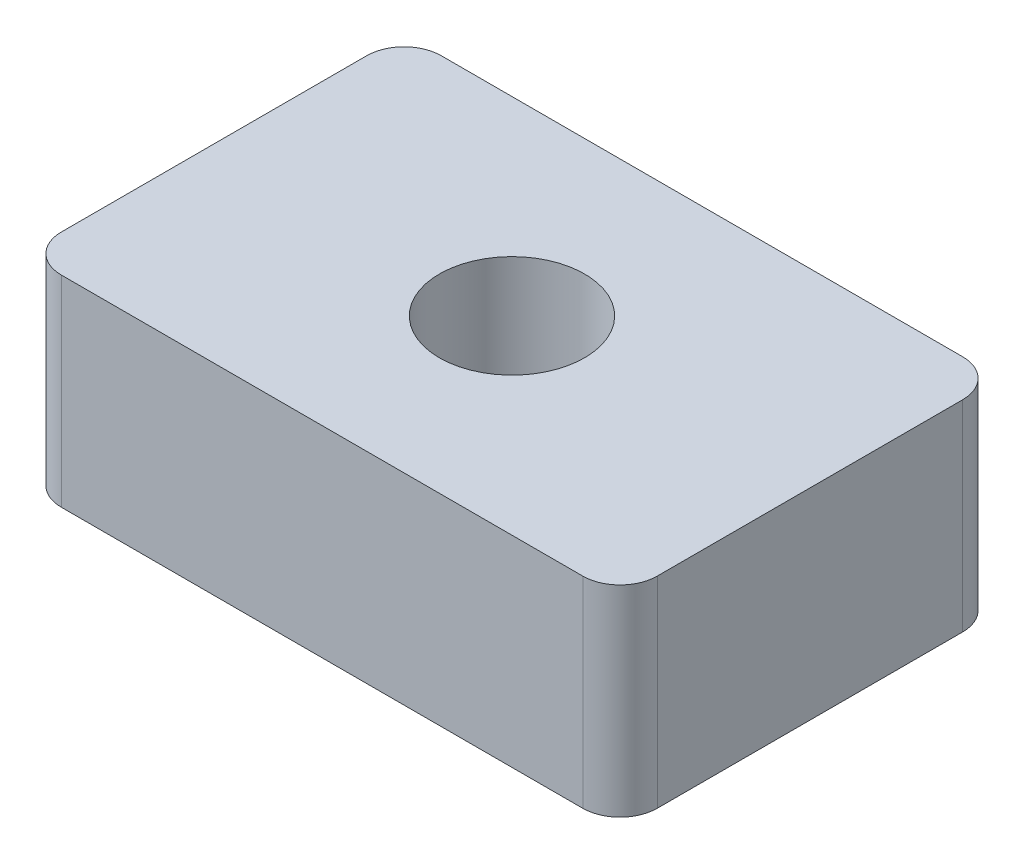
SolidWorks part; units mm, degrees
ref_plane "Alzado" through (0, 0, 0) normal (0, 0, 1) x (1, 0, 0)
ref_plane "Planta" through (0, 0, 0) normal (0, 1, 0) x (1, 0, 0)
ref_plane "Vista lateral" through (0, 0, 0) normal (1, 0, 0) x (0, 0, -1)
sketch "Croquis1" plane through (0, 0, 0) normal (0, 1, 0) x (1, 0, 0)
  line L1 (0, 0) -> (80, 0)
  line L2 (0, 0) -> (0, 51)
  line L3 (0, 51) -> (80, 51)
  line L4 (80, 0) -> (80, 51)
  dimension "D1" = 51
  dimension "D2" = 80
extrude "Saliente-Extruir1" add sketch "Croquis1" along normal blind 27
sketch "Croquis2" plane through (0, 27, 0) normal (0, 1, 0) x (1, 0, 0)
  line L0 (0, 25.5) -> (80, 25.5) construction
  line L1 (0, 51) -> (0, 0) construction
  line L2 (80, 0) -> (80, 51) construction
  line L3 (40, 51) -> (40, 0) construction
  line L4 (80, 51) -> (0, 51) construction
  line L5 (0, 0) -> (80, 0) construction
  circle A0 centre (40, 25.5) radius 9.75
  point P14 (0, 0)
  dimension "D1" = 19.5
extrude "Cortar-Extruir1" cut sketch "Croquis2" against normal blind 27
fillet "Redondeo1" radius 5 4 edges at (0, 13.5, -51) (80, 13.5, -51) (80, 13.5, 0) (0, 13.5, 0)
